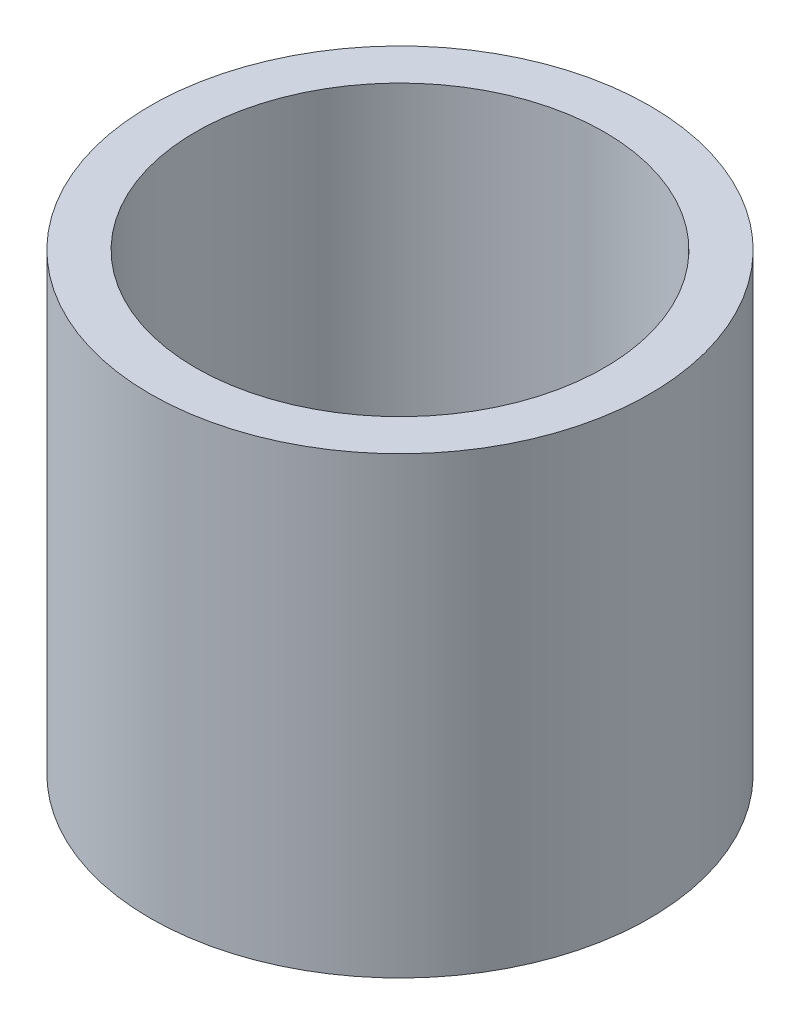
SolidWorks part; units mm, degrees
material "Markforged"
ref_plane "Front Plane" through (0, 0, 0) normal (0, 0, 1) x (1, 0, 0)
ref_plane "Top Plane" through (0, 0, 0) normal (0, 1, 0) x (1, 0, 0)
ref_plane "Right Plane" through (0, 0, 0) normal (1, 0, 0) x (0, 0, -1)
other "Bounding Box"
ref_plane "Default Plane" through (-8.9266, -12.7485, 0) normal (-0.1736, 0.9848, 0) x (0.9848, 0.1736, 0)
sketch "Sketch1" plane through (0, 0, 0) normal (0, 1, 0) x (1, 0, 0)
  circle A0 centre (0, 0) radius 8.7312
  circle A1 centre (0, 0) radius 7.1438
  dimension "D1" = 17.4625
  dimension "D2" = 14.2875
extrude "Boss-Extrude1" add sketch "Sketch1" along normal blind 15.875
